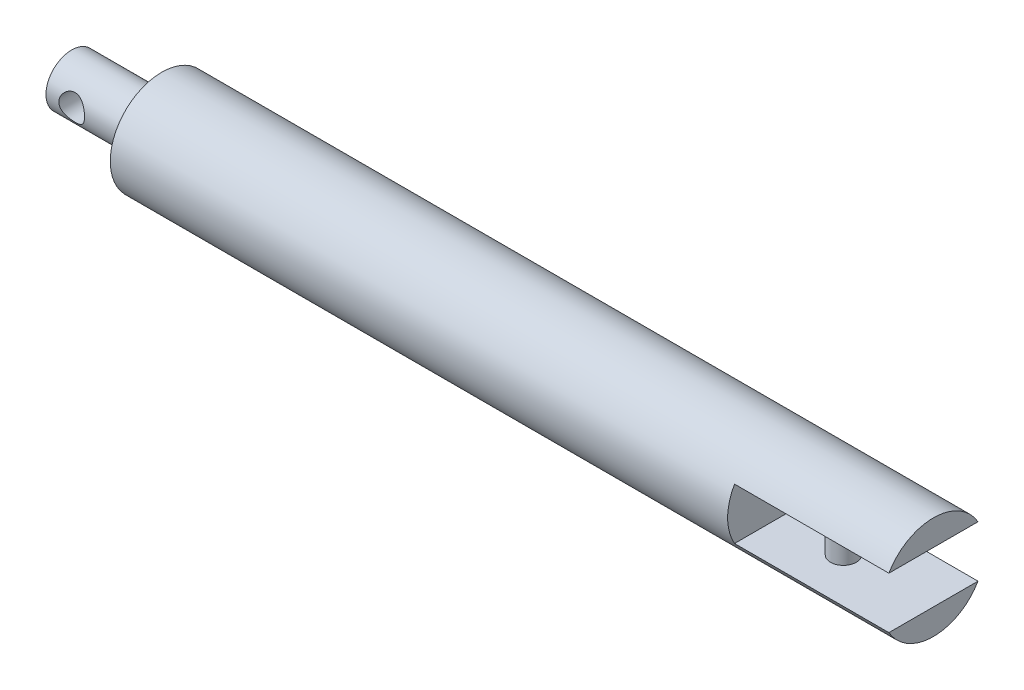
SolidWorks part; units mm, degrees
ref_plane "Front Plane" through (0, 0, 0) normal (0, 0, 1) x (1, 0, 0)
ref_plane "Top Plane" through (0, 0, 0) normal (0, 1, 0) x (1, 0, 0)
ref_plane "Right Plane" through (0, 0, 0) normal (1, 0, 0) x (0, 0, -1)
sketch "Sketch1" plane through (0, 0, 0) normal (1, 0, 0) x (0, 0, -1)
  circle A0 centre (0, 0) radius 2
extrude "Boss-Extrude1" add sketch "Sketch1" along normal blind 7 contours A0
ref_plane "Plane1" through (0, 0, 2) normal (0, 0, 1) x (1, 0, 0)
sketch "Sketch2" plane through (0, 0, 2) normal (0, 0, 1) x (1, 0, 0)
  circle A0 centre (2, 0) radius 1
extrude "Cut-Extrude1" cut sketch "Sketch2" against normal blind 4 contours A0
sketch "Sketch3" plane through (7, 0, 0) normal (1, 0, 0) x (0, 0, -1)
  circle A0 centre (0, 0) radius 4
extrude "Boss-Extrude2" add sketch "Sketch3" along normal blind 60
sketch "Sketch4" plane through (67, 0, 0) normal (1, 0, 0) x (0, 0, -1)
  line L1 (-4.594, -2) -> (4.358, -2)
  line L2 (-4.594, -2) -> (-4.594, 2)
  line L3 (-4.594, 2) -> (4.358, 2)
  line L4 (4.358, -2) -> (4.358, 2)
extrude "Cut-Extrude2" cut sketch "Sketch4" against normal blind 12
sketch "Sketch5" plane through (0, -2, 0) normal (0, 1, 0) x (1, 0, 0)
  circle A0 centre (60, 0) radius 1
extrude "Boss-Extrude3" add sketch "Sketch5" along normal blind 4 contours A0
